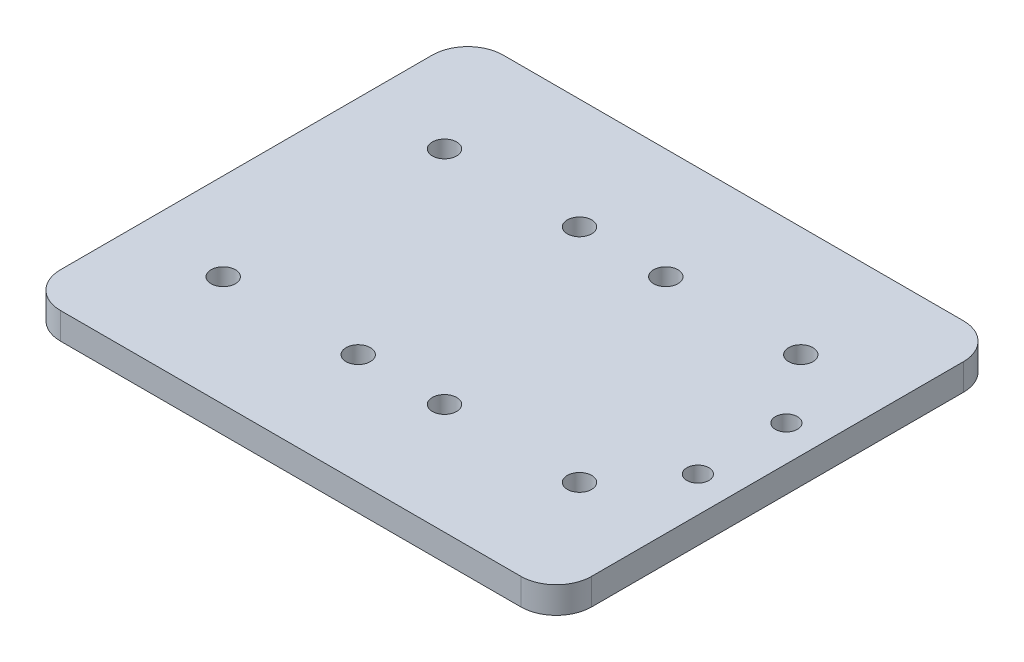
SolidWorks part; units mm, degrees
ref_plane "Plano frontal" through (0, 0, 0) normal (0, 0, 1) x (1, 0, 0)
ref_plane "Plano superior" through (0, 0, 0) normal (0, 1, 0) x (1, 0, 0)
ref_plane "Plano direito" through (0, 0, 0) normal (1, 0, 0) x (0, 0, -1)
sketch "Esboço1" plane through (0, 0, 0) normal (0, 1, 0) x (1, 0, 0)
  line L1 (-60, 50) -> (60, 50)
  line L2 (-60, 50) -> (-60, -50)
  line L3 (-60, -50) -> (60, -50)
  line L4 (60, 50) -> (60, -50)
  line L5 (-60, 50) -> (60, -50) construction
  line L6 (-60, -50) -> (60, 50) construction
  point P0 (0, 0)
  dimension "D1" = 120
  dimension "D2" = 100
extrude "Ressalto-extrusão1" add sketch "Esboço1" along normal blind 6
sketch "Esboço2" plane through (0, 6, 0) normal (0, 1, 0) x (1, 0, 0)
  line L0 (0, 50) -> (0, -50) construction
  line L1 (9.75, 25) -> (40.25, 25) construction
  line L2 (60, 50) -> (-60, 50) construction
  line L3 (-60, -50) -> (60, -50) construction
  circle A0 centre (9.75, 25) radius 2.75
  circle A1 centre (40.25, 25) radius 2.75
  circle A2 centre (9.75, -25) radius 2.75
  circle A7 centre (40.25, -25) radius 2.75
  circle A8 centre (-40.25, -25) radius 2.75
  circle A9 centre (-9.75, -25) radius 2.75
  circle A10 centre (-40.25, 25) radius 2.75
  circle A11 centre (-9.75, 25) radius 2.75
  point P7 (25, 25)
  dimension "D1" = 5.5
  dimension "D2" = 50
  dimension "D3" = 30.5
  dimension "D4" = 25
  dimension "D5" = 25
extrude "Corte-extrusão1" cut sketch "Esboço2" against normal through all
fillet "Filete1" radius 8 4 edges at (-60, 3, -50) (60, 3, -50) (60, 3, 50) (-60, 3, 50)
sketch "Esboço3" plane through (0, 6, 0) normal (0, 1, 0) x (1, 0, 0)
  line L0 (60, -42) -> (60, 42) construction
  circle A0 centre (52, 10) radius 2.5
  circle A1 centre (52, -10) radius 2.5
  circle A2 centre (40.25, 25) radius 2.75 construction
  dimension "D1" = 5
  dimension "D3" = 15
  dimension "D2" = 8
  dimension "D4" = 20
extrude "Corte-extrusão2" cut sketch "Esboço3" against normal through all
